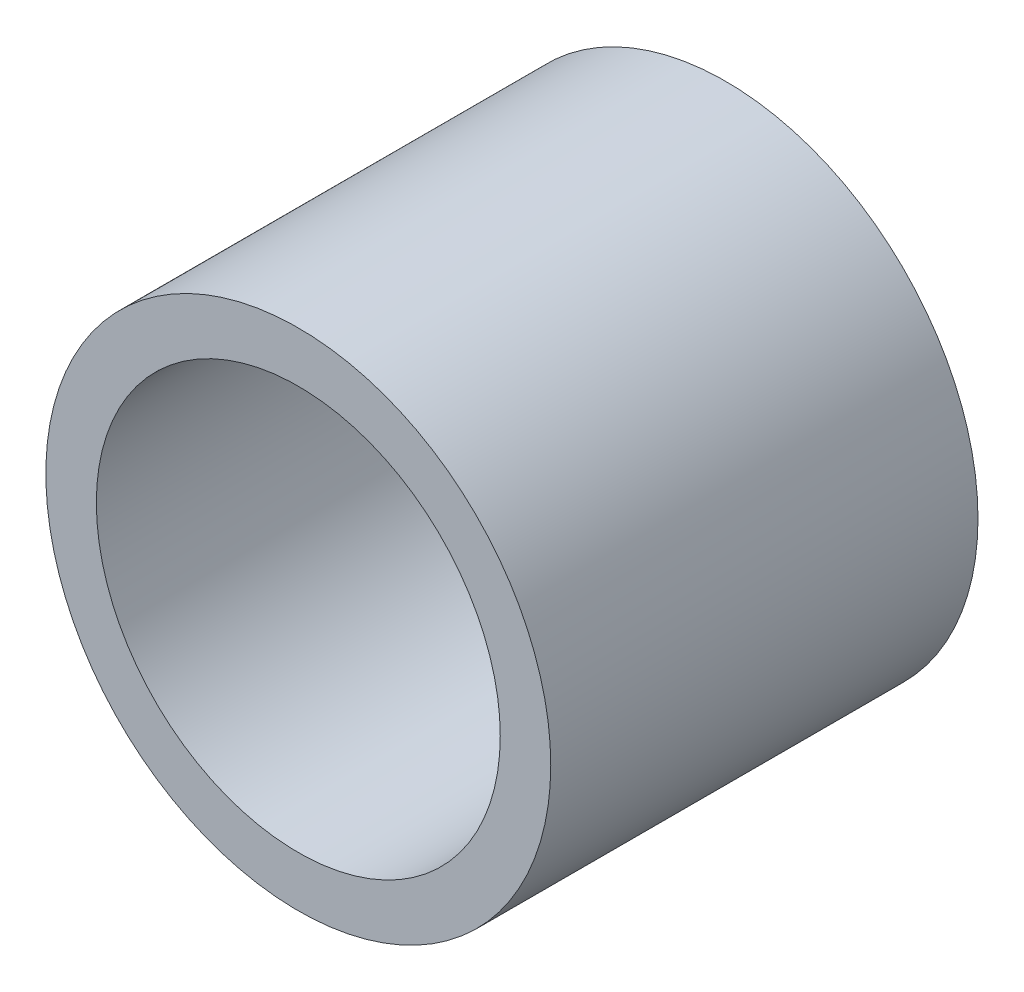
SolidWorks part; units mm, degrees
ref_plane "Alzado" through (0, 0, 0) normal (0, 0, 1) x (1, 0, 0)
ref_plane "Planta" through (0, 0, 0) normal (0, 1, 0) x (1, 0, 0)
ref_plane "Vista lateral" through (0, 0, 0) normal (1, 0, 0) x (0, 0, -1)
sketch "Croquis1" plane through (0, 0, 0) normal (0, 0, 1) x (1, 0, 0)
  circle A0 centre (0, 0) radius 2.6
  circle A1 centre (0, 0) radius 3.25
  dimension "D1" = 5.2
  dimension "D2" = 6.5
extrude "Saliente-Extruir1" add sketch "Croquis1" against normal blind 5.5
